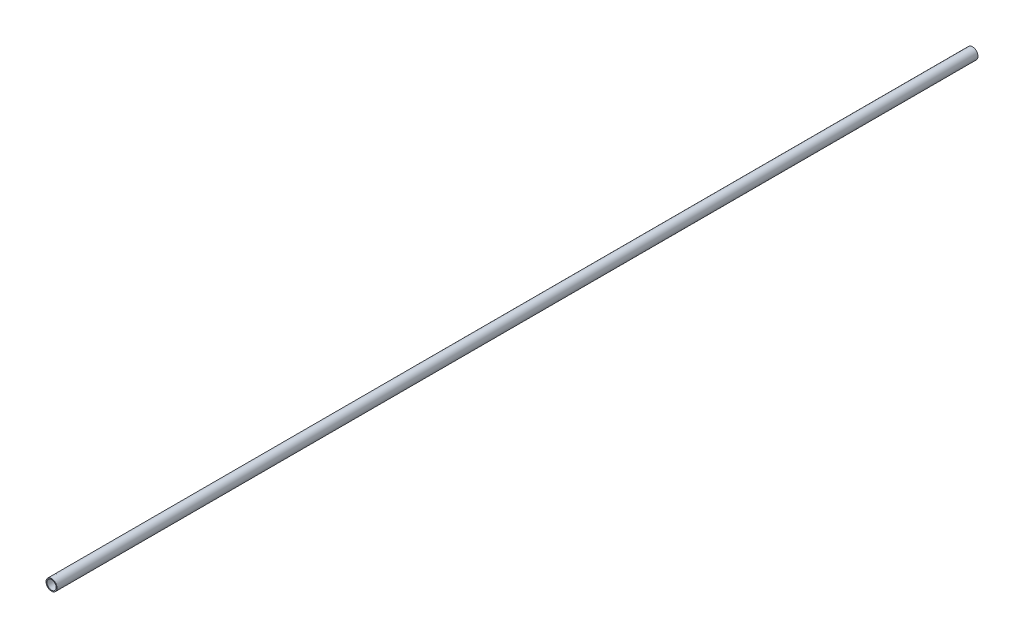
SolidWorks part; units mm, degrees
material "Poltrusion Carbon Fiber"
ref_plane "Front Plane" through (0, 0, 0) normal (0, 0, 1) x (1, 0, 0)
ref_plane "Top Plane" through (0, 0, 0) normal (0, 1, 0) x (1, 0, 0)
ref_plane "Right Plane" through (0, 0, 0) normal (1, 0, 0) x (0, 0, -1)
sketch "Эскиз1" plane through (0, 0, 0) normal (0, 0, 1) x (1, 0, 0)
  circle A0 centre (0, 0) radius 6
  circle A1 centre (0, 0) radius 5
  dimension "D1" = 12
  dimension "D2" = 1
extrude "Бобышка-Вытянуть1" add sketch "Эскиз1" along normal mid plane 1000
